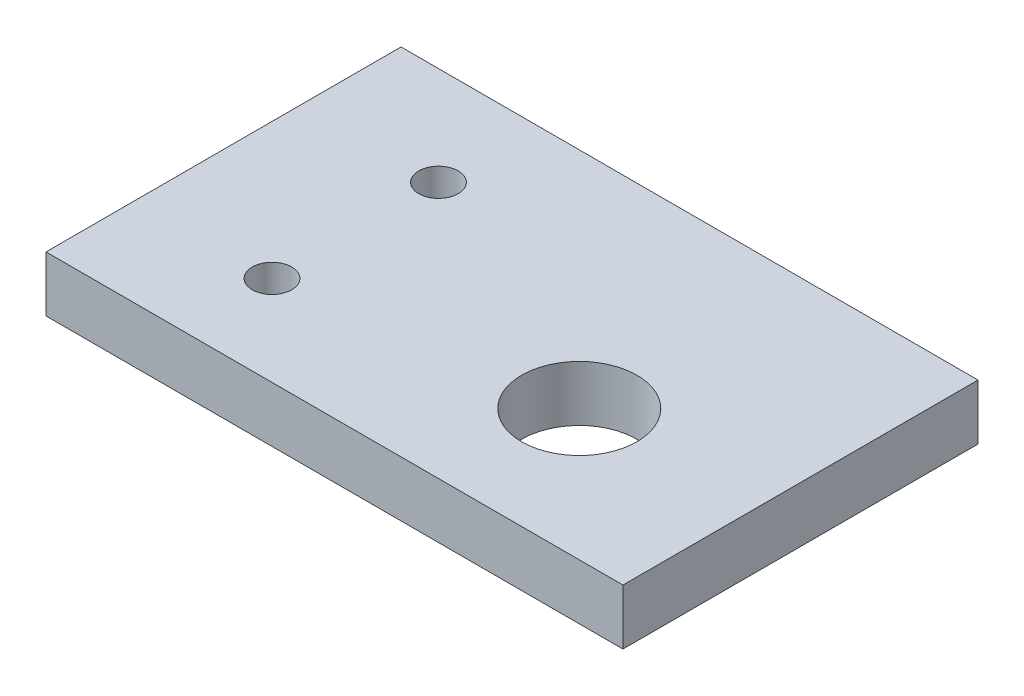
SolidWorks part; units mm, degrees
ref_plane "Front Plane" through (0, 0, 0) normal (0, 0, 1) x (1, 0, 0)
ref_plane "Top Plane" through (0, 0, 0) normal (0, 1, 0) x (1, 0, 0)
ref_plane "Right Plane" through (0, 0, 0) normal (1, 0, 0) x (0, 0, -1)
sketch "Sketch1" plane through (0, 0, 0) normal (0, 1, 0) x (1, 0, 0)
  line L1 (0, 0) -> (33.02, 0)
  line L3 (0, 20.32) -> (33.02, 20.32)
  line L4 (33.02, 0) -> (33.02, 20.32)
  line L6 (0, 0) -> (0, 20.32)
  circle A0 centre (23.02, 7.5) radius 3.3
  dimension "D3" = 6.6
  dimension "D1" = 20.32
  dimension "D2" = 33.02
  dimension "D8" = 7.5
  dimension "D9" = 10
extrude "Boss-Extrude1" add sketch "Sketch1" along normal blind 3.175
sketch "Sketch2" plane through (0, 3.175, 0) normal (0, 1, 0) x (1, 0, 0)
  line L0 (0, 0) -> (33.02, 0) construction
  line L1 (33.02, 0) -> (33.02, 20.32) construction
  circle A0 centre (7.78, 5.1562) radius 1.1303
  circle A1 centre (7.78, 14.6812) radius 1.1303
  dimension "D1" = 2.2606
  dimension "D2" = 5.1562
  dimension "D3" = 25.24
  dimension "D4" = 9.525
extrude "Cut-Extrude1" cut sketch "Sketch2" against normal through all
